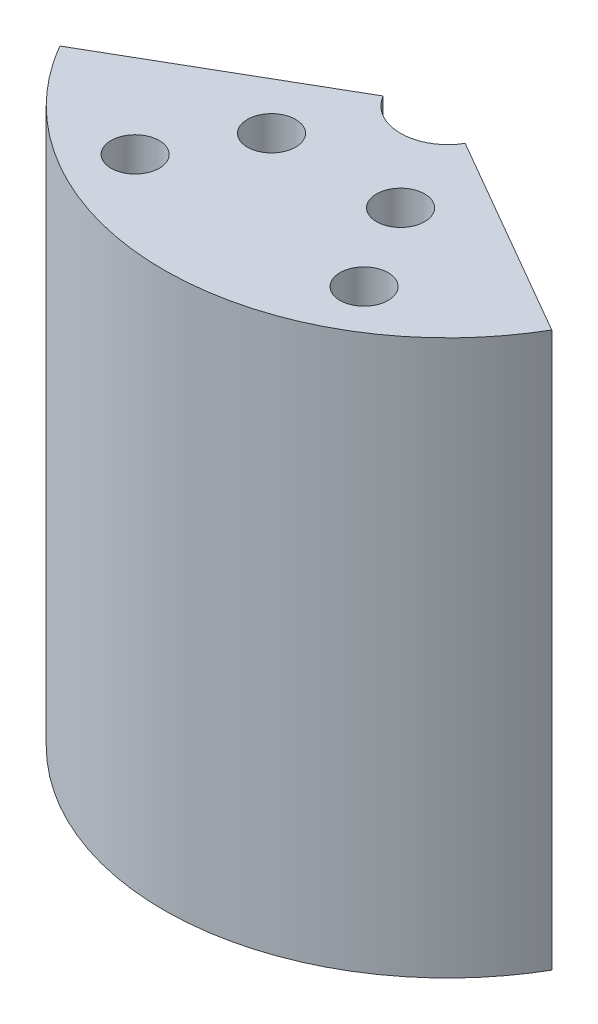
SolidWorks part; units mm, degrees
ref_plane "Front Plane" through (0, 0, 0) normal (0, 0, 1) x (1, 0, 0)
ref_plane "Top Plane" through (0, 0, 0) normal (0, 1, 0) x (1, 0, 0)
ref_plane "Right Plane" through (0, 0, 0) normal (1, 0, 0) x (0, 0, -1)
curve "Curve5"
  spline degree 1 poles (33250, -157953.272, 57590.689) (36750, -157953.272, 63652.867) knots 0 0 1 1
curve "Curve6"
  spline degree 1 poles (-33250, -157953.272, 57590.689) (-36750, -157953.272, 63652.867) knots 0 0 1 1
curve "Curve7"
  spline degree 1 poles (33250, 3112.16, 57590.689) (36750, 3112.16, 63652.867) knots 0 0 1 1
curve "Curve9"
  spline degree 1 poles (-33250, 3112.16, 57590.689) (-36750, 3112.16, 63652.867) knots 0 0 1 1
curve "Curve10"
  spline degree 1 poles (18750, -157953.272, 32475.953) (22250, -157953.272, 38538.13) knots 0 0 1 1
curve "Curve11"
  spline degree 1 poles (-18750, -157953.272, 32475.953) (-22250, -157953.272, 38538.13) knots 0 0 1 1
curve "Curve12"
  spline degree 1 poles (18750, 3112.16, 32475.953) (22250, 3112.16, 38538.13) knots 0 0 1 1
curve "Curve13"
  spline degree 1 poles (-18750, 3112.16, 32475.953) (-22250, 3112.16, 38538.13) knots 0 0 1 1
curve "Curve16"
  spline degree 1 poles (71447.096, -157953.272, 41250) (11907.849, -157953.272, 6875) knots 0 0 1 1
curve "Curve17"
  spline degree 1 poles (-71447.096, -157953.272, 41250) (-11907.849, -157953.272, 6875) knots 0 0 1 1
curve "Curve18"
  spline degree 1 poles (71447.096, 3112.16, 41250) (11907.849, 3112.16, 6875) knots 0 0 1 1
curve "Curve19"
  spline degree 1 poles (-11907.849, 3112.16, 6875) (-71447.096, 3112.16, 41250) knots 0 0 1 1
curve "Curve20"
  spline degree 1 poles (67826.113, -157953.272, -46966.673) (0, -157953.272, 0) knots 0 0 1 1
curve "Curve25"
  spline degree 1 poles (67826.113, 3112.16, -46966.673) (0, 3112.16, 0) knots 0 0 1 1
curve "Curve27"
  spline degree 3 poles (67826.113, 0, -46966.673) (71832.8446, 0, -40036.3374) (83609.5717, 0, -19666.4498) (93574.8958, 0, 18499.4968) (99605.6216, 0, 58154.7721) (101018.9906, 0, 82777.6883) (101543.573, 0, 91916.667) knots 0 0 0 0 0.165944 0.487747 0.809874 1 1 1 1
curve "Curve29"
  spline degree 3 poles (71447.096, -157953.272, 41250) (70846.8209, -157953.272, 42260.6958) (69646.2708, -157953.272, 44282.0874) (67683.2549, -157953.272, 47213.0963) (65605.9749, -157953.272, 50063.2727) (63406.3449, -157953.272, 52820.5514) (61091.5637, -157953.272, 55481.7315) (58665.0093, -157953.272, 58041.4616) (56131.3417, -157953.272, 60495.1976) (53495.1291, -157953.272, 62838.4229) (50761.2001, -157953.272, 65066.8628) (47934.5481, -157953.272, 67176.4488) (45020.3357, -157953.272, 69163.3252) (42023.8854, -157953.272, 71023.8629) (38950.6723, -157953.272, 72754.6647) (35806.3094, -157953.272, 74352.5684) (32596.5398, -157953.272, 75814.6529) (29327.2283, -157953.272, 77138.2518) (26004.3449, -157953.272, 78320.9429) (22633.9607, -157953.272, 79360.5703) (19222.2314, -157953.272, 80255.2301) (15775.3895, -157953.272, 81003.2908) (12299.7315, -157953.272, 81603.3869) (8801.6058, -157953.272, 82054.4198) (5287.4029, -157953.272, 82355.5679) (1763.5414, -157953.272, 82506.2784) (-1763.5414, -157953.272, 82506.2784) (-5287.4029, -157953.272, 82355.5679) (-8801.6058, -157953.272, 82054.4198) (-12299.7315, -157953.272, 81603.3869) (-15775.3895, -157953.272, 81003.2908) (-19222.2314, -157953.272, 80255.2301) (-22633.9607, -157953.272, 79360.5703) (-26004.3449, -157953.272, 78320.9429) (-29327.2283, -157953.272, 77138.2518) (-32596.5398, -157953.272, 75814.6529) (-35806.3094, -157953.272, 74352.5684) (-38950.6723, -157953.272, 72754.6647) (-42023.8854, -157953.272, 71023.8629) (-45020.3357, -157953.272, 69163.3252) (-47934.5481, -157953.272, 67176.4488) (-50761.2001, -157953.272, 65066.8628) (-53495.1291, -157953.272, 62838.4229) (-56131.3417, -157953.272, 60495.1976) (-58665.0093, -157953.272, 58041.4616) (-61091.5637, -157953.272, 55481.7315) (-63406.3449, -157953.272, 52820.5514) (-65605.9749, -157953.272, 50063.2727) (-67683.2549, -157953.272, 47213.0963) (-69646.2708, -157953.272, 44282.0874) (-70846.8209, -157953.272, 42260.6958) (-71447.096, -157953.272, 41250) knots 0 0 0 0 0.020408 0.040816 0.061224 0.081633 0.102041 0.122449 0.142857 0.163265 0.183673 0.204082 0.22449 0.244898 0.265306 0.285714 0.306122 0.326531 0.346939 0.367347 0.387755 0.408163 0.428571 0.44898 0.469388 0.489796 0.510204 0.530612 0.55102 0.571429 0.591837 0.612245 0.632653 0.653061 0.673469 0.693878 0.714286 0.734694 0.755102 0.77551 0.795918 0.816327 0.836735 0.857143 0.877551 0.897959 0.918367 0.938776 0.959184 0.979592 1 1 1 1
curve "Curve30"
  spline degree 3 poles (11907.849, -157953.272, 6875) (11807.803, -157953.272, 7043.4492) (11607.711, -157953.272, 7380.3474) (11280.5433, -157953.272, 7868.8496) (10934.3294, -157953.272, 8343.8788) (10567.7239, -157953.272, 8803.4251) (10181.9265, -157953.272, 9246.955) (9777.5017, -157953.272, 9673.5774) (9355.2232, -157953.272, 10082.5328) (8915.8543, -157953.272, 10473.0703) (8460.1999, -157953.272, 10844.4775) (7989.0912, -157953.272, 11196.0746) (7503.3891, -157953.272, 11527.2202) (7003.9814, -157953.272, 11837.3112) (6491.7785, -157953.272, 12125.7774) (5967.7179, -157953.272, 12392.0944) (5432.7569, -157953.272, 12635.7764) (4887.871, -157953.272, 12856.3745) (4334.0575, -157953.272, 13053.4915) (3772.3267, -157953.272, 13226.7617) (3203.705, -157953.272, 13375.8712) (2629.2315, -157953.272, 13500.548) (2049.9553, -157953.272, 13600.5649) (1466.9345, -157953.272, 13675.7363) (881.234, -157953.272, 13725.9278) (293.9237, -157953.272, 13751.0464) (-293.9237, -157953.272, 13751.0464) (-881.234, -157953.272, 13725.9278) (-1466.9345, -157953.272, 13675.7363) (-2049.9553, -157953.272, 13600.5649) (-2629.2315, -157953.272, 13500.548) (-3203.705, -157953.272, 13375.8712) (-3772.3267, -157953.272, 13226.7617) (-4334.0575, -157953.272, 13053.4915) (-4887.871, -157953.272, 12856.3745) (-5432.7569, -157953.272, 12635.7764) (-5967.7179, -157953.272, 12392.0944) (-6491.7785, -157953.272, 12125.7774) (-7003.9814, -157953.272, 11837.3112) (-7503.3891, -157953.272, 11527.2202) (-7989.0912, -157953.272, 11196.0746) (-8460.1999, -157953.272, 10844.4775) (-8915.8543, -157953.272, 10473.0703) (-9355.2232, -157953.272, 10082.5328) (-9777.5017, -157953.272, 9673.5774) (-10181.9265, -157953.272, 9246.955) (-10567.7239, -157953.272, 8803.4251) (-10934.3294, -157953.272, 8343.8788) (-11280.5433, -157953.272, 7868.8496) (-11607.711, -157953.272, 7380.3474) (-11807.803, -157953.272, 7043.4492) (-11907.849, -157953.272, 6875) knots 0 0 0 0 0.020408 0.040816 0.061224 0.081633 0.102041 0.122449 0.142857 0.163265 0.183673 0.204082 0.22449 0.244898 0.265306 0.285714 0.306122 0.326531 0.346939 0.367347 0.387755 0.408163 0.428571 0.44898 0.469388 0.489796 0.510204 0.530612 0.55102 0.571429 0.591837 0.612245 0.632653 0.653061 0.673469 0.693878 0.714286 0.734694 0.755102 0.77551 0.795918 0.816327 0.836735 0.857143 0.877551 0.897959 0.918367 0.938776 0.959184 0.979592 1 1 1 1
curve "Curve31"
  spline degree 3 poles (71447.096, 3112.16, 41250) (70846.8209, 3112.16, 42260.6958) (69646.2708, 3112.16, 44282.0874) (67683.2549, 3112.16, 47213.0963) (65605.9749, 3112.16, 50063.2727) (63406.3449, 3112.16, 52820.5514) (61091.5637, 3112.16, 55481.7315) (58665.0093, 3112.16, 58041.4616) (56131.3417, 3112.16, 60495.1976) (53495.1291, 3112.16, 62838.4229) (50761.2001, 3112.16, 65066.8628) (47934.5481, 3112.16, 67176.4488) (45020.3357, 3112.16, 69163.3252) (42023.8854, 3112.16, 71023.8629) (38950.6723, 3112.16, 72754.6647) (35806.3094, 3112.16, 74352.5684) (32596.5398, 3112.16, 75814.6529) (29327.2283, 3112.16, 77138.2518) (26004.3449, 3112.16, 78320.9429) (22633.9607, 3112.16, 79360.5703) (19222.2314, 3112.16, 80255.2301) (15775.3895, 3112.16, 81003.2908) (12299.7315, 3112.16, 81603.3869) (8801.6058, 3112.16, 82054.4198) (5287.4029, 3112.16, 82355.5679) (1763.5414, 3112.16, 82506.2784) (-1763.5414, 3112.16, 82506.2784) (-5287.4029, 3112.16, 82355.5679) (-8801.6058, 3112.16, 82054.4198) (-12299.7315, 3112.16, 81603.3869) (-15775.3895, 3112.16, 81003.2908) (-19222.2314, 3112.16, 80255.2301) (-22633.9607, 3112.16, 79360.5703) (-26004.3449, 3112.16, 78320.9429) (-29327.2283, 3112.16, 77138.2518) (-32596.5398, 3112.16, 75814.6529) (-35806.3094, 3112.16, 74352.5684) (-38950.6723, 3112.16, 72754.6647) (-42023.8854, 3112.16, 71023.8629) (-45020.3357, 3112.16, 69163.3252) (-47934.5481, 3112.16, 67176.4488) (-50761.2001, 3112.16, 65066.8628) (-53495.1291, 3112.16, 62838.4229) (-56131.3417, 3112.16, 60495.1976) (-58665.0093, 3112.16, 58041.4616) (-61091.5637, 3112.16, 55481.7315) (-63406.3449, 3112.16, 52820.5514) (-65605.9749, 3112.16, 50063.2727) (-67683.2549, 3112.16, 47213.0963) (-69646.2708, 3112.16, 44282.0874) (-70846.8209, 3112.16, 42260.6958) (-71447.096, 3112.16, 41250) knots 0 0 0 0 0.020408 0.040816 0.061224 0.081633 0.102041 0.122449 0.142857 0.163265 0.183673 0.204082 0.22449 0.244898 0.265306 0.285714 0.306122 0.326531 0.346939 0.367347 0.387755 0.408163 0.428571 0.44898 0.469388 0.489796 0.510204 0.530612 0.55102 0.571429 0.591837 0.612245 0.632653 0.653061 0.673469 0.693878 0.714286 0.734694 0.755102 0.77551 0.795918 0.816327 0.836735 0.857143 0.877551 0.897959 0.918367 0.938776 0.959184 0.979592 1 1 1 1
curve "Curve32"
  spline degree 3 poles (11907.849, 3112.16, 6875) (11807.803, 3112.16, 7043.4492) (11607.711, 3112.16, 7380.3474) (11280.5433, 3112.16, 7868.8496) (10934.3294, 3112.16, 8343.8788) (10567.7239, 3112.16, 8803.4251) (10181.9265, 3112.16, 9246.955) (9777.5017, 3112.16, 9673.5774) (9355.2232, 3112.16, 10082.5328) (8915.8543, 3112.16, 10473.0703) (8460.1999, 3112.16, 10844.4775) (7989.0912, 3112.16, 11196.0746) (7503.3891, 3112.16, 11527.2202) (7003.9814, 3112.16, 11837.3112) (6491.7785, 3112.16, 12125.7774) (5967.7179, 3112.16, 12392.0944) (5432.7569, 3112.16, 12635.7764) (4887.871, 3112.16, 12856.3745) (4334.0575, 3112.16, 13053.4915) (3772.3267, 3112.16, 13226.7617) (3203.705, 3112.16, 13375.8712) (2629.2315, 3112.16, 13500.548) (2049.9553, 3112.16, 13600.5649) (1466.9345, 3112.16, 13675.7363) (881.234, 3112.16, 13725.9278) (293.9237, 3112.16, 13751.0464) (-293.9237, 3112.16, 13751.0464) (-881.234, 3112.16, 13725.9278) (-1466.9345, 3112.16, 13675.7363) (-2049.9553, 3112.16, 13600.5649) (-2629.2315, 3112.16, 13500.548) (-3203.705, 3112.16, 13375.8712) (-3772.3267, 3112.16, 13226.7617) (-4334.0575, 3112.16, 13053.4915) (-4887.871, 3112.16, 12856.3745) (-5432.7569, 3112.16, 12635.7764) (-5967.7179, 3112.16, 12392.0944) (-6491.7785, 3112.16, 12125.7774) (-7003.9814, 3112.16, 11837.3112) (-7503.3891, 3112.16, 11527.2202) (-7989.0912, 3112.16, 11196.0746) (-8460.1999, 3112.16, 10844.4775) (-8915.8543, 3112.16, 10473.0703) (-9355.2232, 3112.16, 10082.5328) (-9777.5017, 3112.16, 9673.5774) (-10181.9265, 3112.16, 9246.955) (-10567.7239, 3112.16, 8803.4251) (-10934.3294, 3112.16, 8343.8788) (-11280.5433, 3112.16, 7868.8496) (-11607.711, 3112.16, 7380.3474) (-11807.803, 3112.16, 7043.4492) (-11907.849, 3112.16, 6875) knots 0 0 0 0 0.020408 0.040816 0.061224 0.081633 0.102041 0.122449 0.142857 0.163265 0.183673 0.204082 0.22449 0.244898 0.265306 0.285714 0.306122 0.326531 0.346939 0.367347 0.387755 0.408163 0.428571 0.44898 0.469388 0.489796 0.510204 0.530612 0.55102 0.571429 0.591837 0.612245 0.632653 0.653061 0.673469 0.693878 0.714286 0.734694 0.755102 0.77551 0.795918 0.816327 0.836735 0.857143 0.877551 0.897959 0.918367 0.938776 0.959184 0.979592 1 1 1 1
curve "Curve33"
  spline degree 3 poles (66490.2119, 3112.16, -1397.4309) (66504.8941, 3112.16, 0) (66490.2119, 3112.16, 1397.4309) (66446.1664, 3112.16, 2794.2445) (66372.7844, 3112.16, 4189.8244) (66270.0898, 3112.16, 5583.554) (66138.1343, 3112.16, 6974.8185) (65976.9749, 3112.16, 8363.0031) (65786.6803, 3112.16, 9747.4946) (65567.3377, 3112.16, 11127.6818) (65319.041, 3112.16, 12502.9553) (65041.9019, 3112.16, 13872.7081) (64736.0413, 3112.16, 15236.3351) (64401.5954, 3112.16, 16593.2339) (64038.7134, 3112.16, 17942.8059) (63647.5507, 3112.16, 19284.4543) (63228.2857, 3112.16, 20617.588) (62781.0993, 3112.16, 21941.6172) (62306.1905, 3112.16, 23255.9573) (61803.7692, 3112.16, 24560.0284) (61274.0587, 3112.16, 25853.255) (60717.2893, 3112.16, 27135.065) (60133.7098, 3112.16, 28404.8932) (59523.5764, 3112.16, 29662.1782) (58887.16, 3112.16, 30906.3655) (58224.7399, 3112.16, 32136.9054) (57536.6095, 3112.16, 33353.2547) (56823.072, 3112.16, 34554.8758) (56084.4435, 3112.16, 35741.2383) (55321.0501, 3112.16, 36911.8188) (54533.2289, 3112.16, 38066.1005) (53721.3251, 3112.16, 39203.5719) (52885.7025, 3112.16, 40323.734) (52026.7247, 3112.16, 41426.0884) (51144.7752, 3112.16, 42510.1518) (50240.2403, 3112.16, 43575.4429) (49313.5212, 3112.16, 44621.493) (48365.0267, 3112.16, 45647.8394) (47395.1749, 3112.16, 46654.0286) (46404.3952, 3112.16, 47639.6169) (45393.1248, 3112.16, 48604.1691) (44361.8098, 3112.16, 49547.2583) (43310.9062, 3112.16, 50468.4694) (42240.8781, 3112.16, 51367.3954) (41152.1964, 3112.16, 52243.6381) (40045.3432, 3112.16, 53096.8111) (38920.8085, 3112.16, 53926.5402) (37779.0861, 3112.16, 54732.4548) (36620.6825, 3112.16, 55514.203) (35446.1064, 3112.16, 56271.4348) (34255.8804, 3112.16, 57003.8213) (33050.527, 3112.16, 57711.0353) (31830.5798, 3112.16, 58392.7664) (30596.5766, 3112.16, 59048.7127) (29349.0632, 3112.16, 59678.5849) (28088.59, 3112.16, 60282.1047) (26815.7134, 3112.16, 60859.0048) (25530.9963, 3112.16, 61409.0322) (24235.0054, 3112.16, 61931.9434) (22928.3123, 3112.16, 62427.5048) (21611.4956, 3112.16, 62895.5034) (20285.1348, 3112.16, 63335.7256) (18949.8178, 3112.16, 63747.9838) (17606.1327, 3112.16, 64132.0909) (16254.6729, 3112.16, 64487.8789) (14896.0357, 3112.16, 64815.192) (13530.8207, 3112.16, 65113.8844) (12159.6307, 3112.16, 65383.8224) (10783.0718, 3112.16, 65624.892) (9401.751, 3112.16, 65836.9813) (8016.2791, 3112.16, 66019.9986) (6627.2675, 3112.16, 66173.864) (5235.3292, 3112.16, 66298.5095) (3841.079, 3112.16, 66393.878) (2445.1328, 3112.16, 66459.9303) (1048.1071, 3112.16, 66496.6348) (-349.3818, 3112.16, 66503.9764) (-1746.7163, 3112.16, 66481.9516) (-3143.2793, 3112.16, 66430.5711) (-4538.4543, 3112.16, 66349.856) (-5931.6255, 3112.16, 66239.8427) (-7322.1776, 3112.16, 66100.5811) (-8709.4961, 3112.16, 65932.1289) (-10092.9687, 3112.16, 65734.5651) (-11471.9844, 3112.16, 65507.973) (-12845.9346, 3112.16, 65252.455) (-14214.213, 3112.16, 64968.1248) (-15576.2141, 3112.16, 64655.1041) (-16931.3373, 3112.16, 64313.5351) (-18278.984, 3112.16, 63943.5672) (-19618.5592, 3112.16, 63545.3624) (-20949.4714, 3112.16, 63119.0984) (-22271.1332, 3112.16, 62664.9628) (-23582.9605, 3112.16, 62183.1564) (-24884.3746, 3112.16, 61673.8919) (-26174.8003, 3112.16, 61137.3937) (-27453.6673, 3112.16, 60573.8979) (-28720.4119, 3112.16, 59983.6551) (-29974.4751, 3112.16, 59366.9267) (-31215.3011, 3112.16, 58723.9803) (-32442.3447, 3112.16, 58055.1058) (-33655.0619, 3112.16, 57360.5945) (-34852.9176, 3112.16, 56640.7543) (-36035.3846, 3112.16, 55895.905) (-37201.9373, 3112.16, 55126.371) (-38352.0641, 3112.16, 54332.4966) (-39485.2547, 3112.16, 53514.6292) (-40601.0113, 3112.16, 52673.1326) (-41698.8386, 3112.16, 51808.3759) (-42778.2531, 3112.16, 50920.7428) (-43838.7775, 3112.16, 50010.624) (-44879.9452, 3112.16, 49078.4232) (-45901.2938, 3112.16, 48124.549) (-46902.3737, 3112.16, 47149.4246) (-47882.7441, 3112.16, 46153.482) (-48841.9695, 3112.16, 45137.1576) (-49779.6285, 3112.16, 44100.9028) (-50695.3062, 3112.16, 43045.1738) (-51588.5976, 3112.16, 41970.4371) (-52459.1084, 3112.16, 40877.1672) (-53306.4565, 3112.16, 39765.8486) (-54130.2646, 3112.16, 38636.9692) (-54930.1718, 3112.16, 37491.0295) (-55705.8215, 3112.16, 36328.5336) (-56456.8738, 3112.16, 35149.9966) (-57182.9977, 3112.16, 33955.9394) (-57883.8688, 3112.16, 32746.8867) (-58559.1814, 3112.16, 31523.3751) (-59208.6372, 3112.16, 30285.9439) (-59831.9447, 3112.16, 29035.1377) (-60428.8356, 3112.16, 27771.5118) (-60999.0411, 3112.16, 26495.6222) (-61542.3113, 3112.16, 25208.0329) (-62058.4062, 3112.16, 23909.313) (-62547.0971, 3112.16, 22600.0347) (-63008.1702, 3112.16, 21280.7773) (-63441.4199, 3112.16, 19952.1226) (-63846.6557, 3112.16, 18614.6576) (-64223.6996, 3112.16, 17268.9733) (-64572.3832, 3112.16, 15915.6631) (-64892.554, 3112.16, 14555.3252) (-65184.069, 3112.16, 13188.5596) (-65446.8018, 3112.16, 11815.9708) (-65680.6336, 3112.16, 10438.1641) (-65885.4639, 3112.16, 9055.7486) (-66061.2006, 3112.16, 7669.3342) (-66207.7678, 3112.16, 6279.5334) (-66325.0981, 3112.16, 4886.9592) (-66413.142, 3112.16, 3492.2274) (-66471.8577, 3112.16, 2095.9534) (-66501.2233, 3112.16, 698.7539) (-66501.2233, 3112.16, -698.7539) (-66471.8577, 3112.16, -2095.9534) (-66413.142, 3112.16, -3492.2274) (-66325.0981, 3112.16, -4886.9592) (-66207.7678, 3112.16, -6279.5334) (-66061.2006, 3112.16, -7669.3342) (-65885.4639, 3112.16, -9055.7486) (-65680.6336, 3112.16, -10438.1641) (-65446.8018, 3112.16, -11815.9708) (-65184.069, 3112.16, -13188.5596) (-64892.554, 3112.16, -14555.3252) (-64572.3832, 3112.16, -15915.6631) (-64223.6996, 3112.16, -17268.9733) (-63846.6557, 3112.16, -18614.6576) (-63441.4199, 3112.16, -19952.1226) (-63008.1702, 3112.16, -21280.7773) (-62547.0971, 3112.16, -22600.0347) (-62058.4062, 3112.16, -23909.313) (-61542.3113, 3112.16, -25208.0329) (-60999.0411, 3112.16, -26495.6222) (-60428.8356, 3112.16, -27771.5118) (-59831.9447, 3112.16, -29035.1377) (-59208.6372, 3112.16, -30285.9439) (-58559.1814, 3112.16, -31523.3751) (-57883.8688, 3112.16, -32746.8867) (-57182.9977, 3112.16, -33955.9394) (-56456.8738, 3112.16, -35149.9966) (-55705.8215, 3112.16, -36328.5336) (-54930.1718, 3112.16, -37491.0295) (-54130.2646, 3112.16, -38636.9692) (-53306.4565, 3112.16, -39765.8486) (-52459.1084, 3112.16, -40877.1672) (-51588.5976, 3112.16, -41970.4371) (-50695.3062, 3112.16, -43045.1738) (-49779.6285, 3112.16, -44100.9028) (-48841.9695, 3112.16, -45137.1576) (-47882.7441, 3112.16, -46153.482) (-46902.3737, 3112.16, -47149.4246) (-45901.2938, 3112.16, -48124.549) (-44879.9452, 3112.16, -49078.4232) (-43838.7775, 3112.16, -50010.624) (-42778.2531, 3112.16, -50920.7428) (-41698.8386, 3112.16, -51808.3759) (-40601.0113, 3112.16, -52673.1326) (-39485.2547, 3112.16, -53514.6292) (-38352.0641, 3112.16, -54332.4966) (-37201.9373, 3112.16, -55126.371) (-36035.3846, 3112.16, -55895.905) (-34852.9176, 3112.16, -56640.7543) (-33655.0619, 3112.16, -57360.5945) (-32442.3447, 3112.16, -58055.1058) (-31215.3011, 3112.16, -58723.9803) (-29974.4751, 3112.16, -59366.9267) (-28720.4119, 3112.16, -59983.6551) (-27453.6673, 3112.16, -60573.8979) (-26174.8003, 3112.16, -61137.3937) (-24884.3746, 3112.16, -61673.8919) (-23582.9605, 3112.16, -62183.1564) (-22271.1332, 3112.16, -62664.9628) (-20949.4714, 3112.16, -63119.0984) (-19618.5592, 3112.16, -63545.3624) (-18278.984, 3112.16, -63943.5672) (-16931.3373, 3112.16, -64313.5351) (-15576.2141, 3112.16, -64655.1041) (-14214.213, 3112.16, -64968.1248) (-12845.9346, 3112.16, -65252.455) (-11471.9844, 3112.16, -65507.973) (-10092.9687, 3112.16, -65734.5651) (-8709.4961, 3112.16, -65932.1289) (-7322.1776, 3112.16, -66100.5811) (-5931.6255, 3112.16, -66239.8427) (-4538.4543, 3112.16, -66349.856) (-3143.2793, 3112.16, -66430.5711) (-1746.7163, 3112.16, -66481.9516) (-349.3818, 3112.16, -66503.9764) (1048.1071, 3112.16, -66496.6348) (2445.1328, 3112.16, -66459.9303) (3841.079, 3112.16, -66393.878) (5235.3292, 3112.16, -66298.5095) (6627.2675, 3112.16, -66173.864) (8016.2791, 3112.16, -66019.9986) (9401.751, 3112.16, -65836.9813) (10783.0718, 3112.16, -65624.892) (12159.6307, 3112.16, -65383.8224) (13530.8207, 3112.16, -65113.8844) (14896.0357, 3112.16, -64815.192) (16254.6729, 3112.16, -64487.8789) (17606.1327, 3112.16, -64132.0909) (18949.8178, 3112.16, -63747.9838) (20285.1348, 3112.16, -63335.7256) (21611.4956, 3112.16, -62895.5034) (22928.3123, 3112.16, -62427.5048) (24235.0054, 3112.16, -61931.9434) (25530.9963, 3112.16, -61409.0322) (26815.7134, 3112.16, -60859.0048) (28088.59, 3112.16, -60282.1047) (29349.0632, 3112.16, -59678.5849) (30596.5766, 3112.16, -59048.7127) (31830.5798, 3112.16, -58392.7664) (33050.527, 3112.16, -57711.0353) (34255.8804, 3112.16, -57003.8213) (35446.1064, 3112.16, -56271.4348) (36620.6825, 3112.16, -55514.203) (37779.0861, 3112.16, -54732.4548) (38920.8085, 3112.16, -53926.5402) (40045.3432, 3112.16, -53096.8111) (41152.1964, 3112.16, -52243.6381) (42240.8781, 3112.16, -51367.3954) (43310.9062, 3112.16, -50468.4694) (44361.8098, 3112.16, -49547.2583) (45393.1248, 3112.16, -48604.1691) (46404.3952, 3112.16, -47639.6169) (47395.1749, 3112.16, -46654.0286) (48365.0267, 3112.16, -45647.8394) (49313.5212, 3112.16, -44621.493) (50240.2403, 3112.16, -43575.4429) (51144.7752, 3112.16, -42510.1518) (52026.7247, 3112.16, -41426.0884) (52885.7025, 3112.16, -40323.734) (53721.3251, 3112.16, -39203.5719) (54533.2289, 3112.16, -38066.1005) (55321.0501, 3112.16, -36911.8188) (56084.4435, 3112.16, -35741.2383) (56823.072, 3112.16, -34554.8758) (57536.6095, 3112.16, -33353.2547) (58224.7399, 3112.16, -32136.9054) (58887.16, 3112.16, -30906.3655) (59523.5764, 3112.16, -29662.1782) (60133.7098, 3112.16, -28404.8932) (60717.2893, 3112.16, -27135.065) (61274.0587, 3112.16, -25853.255) (61803.7692, 3112.16, -24560.0284) (62306.1905, 3112.16, -23255.9573) (62781.0993, 3112.16, -21941.6172) (63228.2857, 3112.16, -20617.588) (63647.5507, 3112.16, -19284.4543) (64038.7134, 3112.16, -17942.8059) (64401.5954, 3112.16, -16593.2339) (64736.0413, 3112.16, -15236.3351) (65041.9019, 3112.16, -13872.7081) (65319.041, 3112.16, -12502.9553) (65567.3377, 3112.16, -11127.6818) (65786.6803, 3112.16, -9747.4946) (65976.9749, 3112.16, -8363.0031) (66138.1343, 3112.16, -6974.8185) (66270.0898, 3112.16, -5583.554) (66372.7844, 3112.16, -4189.8244) (66446.1664, 3112.16, -2794.2445) (66490.2119, 3112.16, -1397.4309) (66504.8941, 3112.16, 0) (66490.2119, 3112.16, 1397.4309) knots -0.010033 -0.006689 -0.003344 0 0.003344 0.006689 0.010033 0.013378 0.016722 0.020067 0.023411 0.026756 0.0301 0.033445 0.036789 0.040134 0.043478 0.046823 0.050167 0.053512 0.056856 0.060201 0.063545 0.06689 0.070234 0.073579 0.076923 0.080268 0.083612 0.086957 0.090301 0.093645 0.09699 0.100334 0.103679 0.107023 0.110368 0.113712 0.117057 0.120401 0.123746 0.12709 0.130435 0.133779 0.137124 0.140468 0.143813 0.147157 0.150502 0.153846 0.157191 0.160535 0.16388 0.167224 0.170569 0.173913 0.177258 0.180602 0.183946 0.187291 0.190635 0.19398 0.197324 0.200669 0.204013 0.207358 0.210702 0.214047 0.217391 0.220736 0.22408 0.227425 0.230769 0.234114 0.237458 0.240803 0.244147 0.247492 0.250836 0.254181 0.257525 0.26087 0.264214 0.267559 0.270903 0.274247 0.277592 0.280936 0.284281 0.287625 0.29097 0.294314 0.297659 0.301003 0.304348 0.307692 0.311037 0.314381 0.317726 0.32107 0.324415 0.327759 0.331104 0.334448 0.337793 0.341137 0.344482 0.347826 0.351171 0.354515 0.35786 0.361204 0.364548 0.367893 0.371237 0.374582 0.377926 0.381271 0.384615 0.38796 0.391304 0.394649 0.397993 0.401338 0.404682 0.408027 0.411371 0.414716 0.41806 0.421405 0.424749 0.428094 0.431438 0.434783 0.438127 0.441472 0.444816 0.448161 0.451505 0.454849 0.458194 0.461538 0.464883 0.468227 0.471572 0.474916 0.478261 0.481605 0.48495 0.488294 0.491639 0.494983 0.498328 0.501672 0.505017 0.508361 0.511706 0.51505 0.518395 0.521739 0.525084 0.528428 0.531773 0.535117 0.538462 0.541806 0.545151 0.548495 0.551839 0.555184 0.558528 0.561873 0.565217 0.568562 0.571906 0.575251 0.578595 0.58194 0.585284 0.588629 0.591973 0.595318 0.598662 0.602007 0.605351 0.608696 0.61204 0.615385 0.618729 0.622074 0.625418 0.628763 0.632107 0.635452 0.638796 0.64214 0.645485 0.648829 0.652174 0.655518 0.658863 0.662207 0.665552 0.668896 0.672241 0.675585 0.67893 0.682274 0.685619 0.688963 0.692308 0.695652 0.698997 0.702341 0.705686 0.70903 0.712375 0.715719 0.719064 0.722408 0.725753 0.729097 0.732441 0.735786 0.73913 0.742475 0.745819 0.749164 0.752508 0.755853 0.759197 0.762542 0.765886 0.769231 0.772575 0.77592 0.779264 0.782609 0.785953 0.789298 0.792642 0.795987 0.799331 0.802676 0.80602 0.809365 0.812709 0.816054 0.819398 0.822742 0.826087 0.829431 0.832776 0.83612 0.839465 0.842809 0.846154 0.849498 0.852843 0.856187 0.859532 0.862876 0.866221 0.869565 0.87291 0.876254 0.879599 0.882943 0.886288 0.889632 0.892977 0.896321 0.899666 0.90301 0.906355 0.909699 0.913043 0.916388 0.919732 0.923077 0.926421 0.929766 0.93311 0.936455 0.939799 0.943144 0.946488 0.949833 0.953177 0.956522 0.959866 0.963211 0.966555 0.9699 0.973244 0.976589 0.979933 0.983278 0.986622 0.989967 0.993311 0.996656 1 1.003344 1.006689 1.010033 periodic
curve "Curve34"
  spline degree 3 poles (-71447.096, -157953.272, 41250) (-119654.1141, -167228.3585, 58604.135) (-176188.8326, -178105.7043, 78956.1746) (-151484.4484, -148962.176, 97388.6003) (-147845.433, -144669.264, 100103.741) knots 0 0 0 0 0.852698 1 1 1 1
ref_plane "Plane1" through (0, 3112.16, 0) normal (0, 1, 0) x (-1, 0, 0)
sketch3d "3DSketch3"
  line L0 (0, -157953.272, 0) -> (0, 3112.16, 0) construction
  line L1 (-71447.096, -157953.272, 41250) -> (-11907.849, -157953.272, 6875)
  line L2 (-71447.096, -157953.272, 41250) -> (-11907.849, -157953.272, 6875)
  line L3 (-18750, -157953.272, 32475.953) -> (-22250, -157953.272, 38538.13)
  line L4 (-18750, -157953.272, 32475.953) -> (-22250, -157953.272, 38538.13)
  line L5 (18750, -157953.272, 32475.953) -> (22250, -157953.272, 38538.13)
  line L6 (18750, -157953.272, 32475.953) -> (22250, -157953.272, 38538.13)
  line L7 (33250, -157953.272, 57590.689) -> (36750, -157953.272, 63652.867)
  line L8 (33250, -157953.272, 57590.689) -> (36750, -157953.272, 63652.867)
  line L9 (71447.096, -157953.272, 41250) -> (11907.849, -157953.272, 6875)
  line L10 (71447.096, -157953.272, 41250) -> (11907.849, -157953.272, 6875)
  line L11 (-33250, -157953.272, 57590.689) -> (-36750, -157953.272, 63652.867)
  line L12 (-33250, -157953.272, 57590.689) -> (-36750, -157953.272, 63652.867)
  line L13 (67826.113, -157953.272, -46966.673) -> (0, -157953.272, 0)
  line L14 (67826.113, -157953.272, -46966.673) -> (0, -157953.272, 0)
  line L15 (-11907.849, 3112.16, 6875) -> (-71447.096, 3112.16, 41250)
  line L16 (-11907.849, 3112.16, 6875) -> (-71447.096, 3112.16, 41250)
  line L17 (71447.096, 3112.16, 41250) -> (11907.849, 3112.16, 6875)
  line L18 (71447.096, 3112.16, 41250) -> (11907.849, 3112.16, 6875)
  line L19 (33250, 3112.16, 57590.689) -> (36750, 3112.16, 63652.867)
  line L20 (33250, 3112.16, 57590.689) -> (36750, 3112.16, 63652.867)
  line L21 (18750, 3112.16, 32475.953) -> (22250, 3112.16, 38538.13)
  line L22 (18750, 3112.16, 32475.953) -> (22250, 3112.16, 38538.13)
  line L23 (-18750, 3112.16, 32475.953) -> (-22250, 3112.16, 38538.13)
  line L24 (-18750, 3112.16, 32475.953) -> (-22250, 3112.16, 38538.13)
  line L25 (-33250, 3112.16, 57590.689) -> (-36750, 3112.16, 63652.867)
  line L26 (-33250, 3112.16, 57590.689) -> (-36750, 3112.16, 63652.867)
  line L27 (67826.113, 3112.16, -46966.673) -> (0, 3112.16, 0)
  line L28 (67826.113, 3112.16, -46966.673) -> (0, 3112.16, 0)
  circle A0 centre (33250, -157953.272, 57590.689) radius 7000.0002
  circle A1 centre (18750, -157953.272, 32475.953) radius 6999.9993
  circle A2 centre (-18750, -157953.272, 32475.953) radius 6999.9993
  circle A3 centre (-33250, -157953.272, 57590.689) radius 7000.0002
  spline S1 degree 3 poles (74076.3652, -157953.272, 37000.5832) (72494.0612, -157953.272, 39361.9368) (70573.6651, -157953.272, 42897.3809) (67683.2549, -157953.272, 47213.0963) (65605.9749, -157953.272, 50063.2727) (63406.3449, -157953.272, 52820.5514) (61091.5637, -157953.272, 55481.7315) (58665.0093, -157953.272, 58041.4616) (56131.3417, -157953.272, 60495.1976) (53495.1291, -157953.272, 62838.4229) (50761.2001, -157953.272, 65066.8628) (47934.5481, -157953.272, 67176.4488) (45020.3357, -157953.272, 69163.3252) (42023.8854, -157953.272, 71023.8629) (38950.6723, -157953.272, 72754.6647) (35806.3094, -157953.272, 74352.5684) (32596.5398, -157953.272, 75814.6529) (29327.2283, -157953.272, 77138.2518) (26004.3449, -157953.272, 78320.9429) (22633.9607, -157953.272, 79360.5703) (19222.2314, -157953.272, 80255.2301) (15775.3895, -157953.272, 81003.2908) (12299.7315, -157953.272, 81603.3869) (8801.6058, -157953.272, 82054.4198) (5287.4029, -157953.272, 82355.5679) (1763.5414, -157953.272, 82506.2784) (-1763.5414, -157953.272, 82506.2784) (-5287.4029, -157953.272, 82355.5679) (-8801.6058, -157953.272, 82054.4198) (-12299.7315, -157953.272, 81603.3869) (-15775.3895, -157953.272, 81003.2908) (-19222.2314, -157953.272, 80255.2301) (-22633.9607, -157953.272, 79360.5703) (-26004.3449, -157953.272, 78320.9429) (-29327.2283, -157953.272, 77138.2518) (-32596.5398, -157953.272, 75814.6529) (-35806.3094, -157953.272, 74352.5684) (-38950.6723, -157953.272, 72754.6647) (-42023.8854, -157953.272, 71023.8629) (-45020.3357, -157953.272, 69163.3252) (-47934.5481, -157953.272, 67176.4488) (-50761.2001, -157953.272, 65066.8628) (-53495.1291, -157953.272, 62838.4229) (-56131.3417, -157953.272, 60495.1976) (-58665.0093, -157953.272, 58041.4616) (-61091.5637, -157953.272, 55481.7315) (-63406.3449, -157953.272, 52820.5514) (-65605.9749, -157953.272, 50063.2727) (-67683.2549, -157953.272, 47213.0963) (-70573.6793, -157953.272, 42897.3597) (-72494.0856, -157953.272, 39361.8919) (-74076.4078, -157953.272, 37000.5196) knots -0.028924 -0.028924 -0.028924 -0.028924 0.020408 0.040816 0.061224 0.081633 0.102041 0.122449 0.142857 0.163265 0.183673 0.204082 0.22449 0.244898 0.265306 0.285714 0.306122 0.326531 0.346939 0.367347 0.387755 0.408163 0.428571 0.44898 0.469388 0.489796 0.510204 0.530612 0.55102 0.571429 0.591837 0.612245 0.632653 0.653061 0.673469 0.693878 0.714286 0.734694 0.755102 0.77551 0.795918 0.816327 0.836735 0.857143 0.877551 0.897959 0.918367 0.938776 0.959184 0.979592 1.028925 1.028925 1.028925 1.028925 only from (71447.096, -157953.272, 41250) to (-71447.096, -157953.272, 41250)
  spline S2 degree 3 poles (71447.096, -157953.272, 41250) (70846.8209, -157953.272, 42260.6958) (69646.2708, -157953.272, 44282.0874) (67683.2549, -157953.272, 47213.0963) (65605.9749, -157953.272, 50063.2727) (63406.3449, -157953.272, 52820.5514) (61091.5637, -157953.272, 55481.7315) (58665.0093, -157953.272, 58041.4616) (56131.3417, -157953.272, 60495.1976) (53495.1291, -157953.272, 62838.4229) (50761.2001, -157953.272, 65066.8628) (47934.5481, -157953.272, 67176.4488) (45020.3357, -157953.272, 69163.3252) (42023.8854, -157953.272, 71023.8629) (38950.6723, -157953.272, 72754.6647) (35806.3094, -157953.272, 74352.5684) (32596.5398, -157953.272, 75814.6529) (29327.2283, -157953.272, 77138.2518) (26004.3449, -157953.272, 78320.9429) (22633.9607, -157953.272, 79360.5703) (19222.2314, -157953.272, 80255.2301) (15775.3895, -157953.272, 81003.2908) (12299.7315, -157953.272, 81603.3869) (8801.6058, -157953.272, 82054.4198) (5287.4029, -157953.272, 82355.5679) (1763.5414, -157953.272, 82506.2784) (-1763.5414, -157953.272, 82506.2784) (-5287.4029, -157953.272, 82355.5679) (-8801.6058, -157953.272, 82054.4198) (-12299.7315, -157953.272, 81603.3869) (-15775.3895, -157953.272, 81003.2908) (-19222.2314, -157953.272, 80255.2301) (-22633.9607, -157953.272, 79360.5703) (-26004.3449, -157953.272, 78320.9429) (-29327.2283, -157953.272, 77138.2518) (-32596.5398, -157953.272, 75814.6529) (-35806.3094, -157953.272, 74352.5684) (-38950.6723, -157953.272, 72754.6647) (-42023.8854, -157953.272, 71023.8629) (-45020.3357, -157953.272, 69163.3252) (-47934.5481, -157953.272, 67176.4488) (-50761.2001, -157953.272, 65066.8628) (-53495.1291, -157953.272, 62838.4229) (-56131.3417, -157953.272, 60495.1976) (-58665.0093, -157953.272, 58041.4616) (-61091.5637, -157953.272, 55481.7315) (-63406.3449, -157953.272, 52820.5514) (-65605.9749, -157953.272, 50063.2727) (-67683.2549, -157953.272, 47213.0963) (-69646.2708, -157953.272, 44282.0874) (-70846.8209, -157953.272, 42260.6958) (-71447.096, -157953.272, 41250) knots 0 0 0 0 0.020408 0.040816 0.061224 0.081633 0.102041 0.122449 0.142857 0.163265 0.183673 0.204082 0.22449 0.244898 0.265306 0.285714 0.306122 0.326531 0.346939 0.367347 0.387755 0.408163 0.428571 0.44898 0.469388 0.489796 0.510204 0.530612 0.55102 0.571429 0.591837 0.612245 0.632653 0.653061 0.673469 0.693878 0.714286 0.734694 0.755102 0.77551 0.795918 0.816327 0.836735 0.857143 0.877551 0.897959 0.918367 0.938776 0.959184 0.979592 1 1 1 1
  spline S3 degree 3 poles (15869.0157, -157953.272, 4277.1823) (13030.7225, -157953.272, 4427.9523) (12405.7025, -157953.272, 6188.8468) (11280.5433, -157953.272, 7868.8496) (10934.3294, -157953.272, 8343.8788) (10567.7239, -157953.272, 8803.4251) (10181.9265, -157953.272, 9246.955) (9777.5017, -157953.272, 9673.5774) (9355.2232, -157953.272, 10082.5328) (8915.8543, -157953.272, 10473.0703) (8460.1999, -157953.272, 10844.4775) (7989.0912, -157953.272, 11196.0746) (7503.3891, -157953.272, 11527.2202) (7003.9814, -157953.272, 11837.3112) (6491.7785, -157953.272, 12125.7774) (5967.7179, -157953.272, 12392.0944) (5432.7569, -157953.272, 12635.7764) (4887.871, -157953.272, 12856.3745) (4334.0575, -157953.272, 13053.4915) (3772.3267, -157953.272, 13226.7617) (3203.705, -157953.272, 13375.8712) (2629.2315, -157953.272, 13500.548) (2049.9553, -157953.272, 13600.5649) (1466.9345, -157953.272, 13675.7363) (881.234, -157953.272, 13725.9278) (293.9237, -157953.272, 13751.0464) (-293.9237, -157953.272, 13751.0464) (-881.234, -157953.272, 13725.9278) (-1466.9345, -157953.272, 13675.7363) (-2049.9553, -157953.272, 13600.5649) (-2629.2315, -157953.272, 13500.548) (-3203.705, -157953.272, 13375.8712) (-3772.3267, -157953.272, 13226.7617) (-4334.0575, -157953.272, 13053.4915) (-4887.871, -157953.272, 12856.3745) (-5432.7569, -157953.272, 12635.7764) (-5967.7179, -157953.272, 12392.0944) (-6491.7785, -157953.272, 12125.7774) (-7003.9814, -157953.272, 11837.3112) (-7503.3891, -157953.272, 11527.2202) (-7989.0912, -157953.272, 11196.0746) (-8460.1999, -157953.272, 10844.4775) (-8915.8543, -157953.272, 10473.0703) (-9355.2232, -157953.272, 10082.5328) (-9777.5017, -157953.272, 9673.5774) (-10181.9265, -157953.272, 9246.955) (-10567.7239, -157953.272, 8803.4251) (-10934.3294, -157953.272, 8343.8788) (-11280.5433, -157953.272, 7868.8496) (-12405.7015, -157953.272, 6188.8483) (-13030.7212, -157953.272, 4427.956) (-15869.0059, -157953.272, 4277.1828) knots -0.149332 -0.149332 -0.149332 -0.149332 0.020408 0.040816 0.061224 0.081633 0.102041 0.122449 0.142857 0.163265 0.183673 0.204082 0.22449 0.244898 0.265306 0.285714 0.306122 0.326531 0.346939 0.367347 0.387755 0.408163 0.428571 0.44898 0.469388 0.489796 0.510204 0.530612 0.55102 0.571429 0.591837 0.612245 0.632653 0.653061 0.673469 0.693878 0.714286 0.734694 0.755102 0.77551 0.795918 0.816327 0.836735 0.857143 0.877551 0.897959 0.918367 0.938776 0.959184 0.979592 1.149332 1.149332 1.149332 1.149332 only from (11907.849, -157953.272, 6875) to (-11907.849, -157953.272, 6875)
  spline S4 degree 3 poles (11907.849, -157953.272, 6875) (11807.803, -157953.272, 7043.4492) (11607.711, -157953.272, 7380.3474) (11280.5433, -157953.272, 7868.8496) (10934.3294, -157953.272, 8343.8788) (10567.7239, -157953.272, 8803.4251) (10181.9265, -157953.272, 9246.955) (9777.5017, -157953.272, 9673.5774) (9355.2232, -157953.272, 10082.5328) (8915.8543, -157953.272, 10473.0703) (8460.1999, -157953.272, 10844.4775) (7989.0912, -157953.272, 11196.0746) (7503.3891, -157953.272, 11527.2202) (7003.9814, -157953.272, 11837.3112) (6491.7785, -157953.272, 12125.7774) (5967.7179, -157953.272, 12392.0944) (5432.7569, -157953.272, 12635.7764) (4887.871, -157953.272, 12856.3745) (4334.0575, -157953.272, 13053.4915) (3772.3267, -157953.272, 13226.7617) (3203.705, -157953.272, 13375.8712) (2629.2315, -157953.272, 13500.548) (2049.9553, -157953.272, 13600.5649) (1466.9345, -157953.272, 13675.7363) (881.234, -157953.272, 13725.9278) (293.9237, -157953.272, 13751.0464) (-293.9237, -157953.272, 13751.0464) (-881.234, -157953.272, 13725.9278) (-1466.9345, -157953.272, 13675.7363) (-2049.9553, -157953.272, 13600.5649) (-2629.2315, -157953.272, 13500.548) (-3203.705, -157953.272, 13375.8712) (-3772.3267, -157953.272, 13226.7617) (-4334.0575, -157953.272, 13053.4915) (-4887.871, -157953.272, 12856.3745) (-5432.7569, -157953.272, 12635.7764) (-5967.7179, -157953.272, 12392.0944) (-6491.7785, -157953.272, 12125.7774) (-7003.9814, -157953.272, 11837.3112) (-7503.3891, -157953.272, 11527.2202) (-7989.0912, -157953.272, 11196.0746) (-8460.1999, -157953.272, 10844.4775) (-8915.8543, -157953.272, 10473.0703) (-9355.2232, -157953.272, 10082.5328) (-9777.5017, -157953.272, 9673.5774) (-10181.9265, -157953.272, 9246.955) (-10567.7239, -157953.272, 8803.4251) (-10934.3294, -157953.272, 8343.8788) (-11280.5433, -157953.272, 7868.8496) (-11607.711, -157953.272, 7380.3474) (-11807.803, -157953.272, 7043.4492) (-11907.849, -157953.272, 6875) knots 0 0 0 0 0.020408 0.040816 0.061224 0.081633 0.102041 0.122449 0.142857 0.163265 0.183673 0.204082 0.22449 0.244898 0.265306 0.285714 0.306122 0.326531 0.346939 0.367347 0.387755 0.408163 0.428571 0.44898 0.469388 0.489796 0.510204 0.530612 0.55102 0.571429 0.591837 0.612245 0.632653 0.653061 0.673469 0.693878 0.714286 0.734694 0.755102 0.77551 0.795918 0.816327 0.836735 0.857143 0.877551 0.897959 0.918367 0.938776 0.959184 0.979592 1 1 1 1
  spline S5 degree 3 poles (15869.0157, 3112.16, 4277.1823) (13030.7225, 3112.16, 4427.9523) (12405.7025, 3112.16, 6188.8468) (11280.5433, 3112.16, 7868.8496) (10934.3294, 3112.16, 8343.8788) (10567.7239, 3112.16, 8803.4251) (10181.9265, 3112.16, 9246.955) (9777.5017, 3112.16, 9673.5774) (9355.2232, 3112.16, 10082.5328) (8915.8543, 3112.16, 10473.0703) (8460.1999, 3112.16, 10844.4775) (7989.0912, 3112.16, 11196.0746) (7503.3891, 3112.16, 11527.2202) (7003.9814, 3112.16, 11837.3112) (6491.7785, 3112.16, 12125.7774) (5967.7179, 3112.16, 12392.0944) (5432.7569, 3112.16, 12635.7764) (4887.871, 3112.16, 12856.3745) (4334.0575, 3112.16, 13053.4915) (3772.3267, 3112.16, 13226.7617) (3203.705, 3112.16, 13375.8712) (2629.2315, 3112.16, 13500.548) (2049.9553, 3112.16, 13600.5649) (1466.9345, 3112.16, 13675.7363) (881.234, 3112.16, 13725.9278) (293.9237, 3112.16, 13751.0464) (-293.9237, 3112.16, 13751.0464) (-881.234, 3112.16, 13725.9278) (-1466.9345, 3112.16, 13675.7363) (-2049.9553, 3112.16, 13600.5649) (-2629.2315, 3112.16, 13500.548) (-3203.705, 3112.16, 13375.8712) (-3772.3267, 3112.16, 13226.7617) (-4334.0575, 3112.16, 13053.4915) (-4887.871, 3112.16, 12856.3745) (-5432.7569, 3112.16, 12635.7764) (-5967.7179, 3112.16, 12392.0944) (-6491.7785, 3112.16, 12125.7774) (-7003.9814, 3112.16, 11837.3112) (-7503.3891, 3112.16, 11527.2202) (-7989.0912, 3112.16, 11196.0746) (-8460.1999, 3112.16, 10844.4775) (-8915.8543, 3112.16, 10473.0703) (-9355.2232, 3112.16, 10082.5328) (-9777.5017, 3112.16, 9673.5774) (-10181.9265, 3112.16, 9246.955) (-10567.7239, 3112.16, 8803.4251) (-10934.3294, 3112.16, 8343.8788) (-11280.5433, 3112.16, 7868.8496) (-12405.7015, 3112.16, 6188.8483) (-13030.7212, 3112.16, 4427.956) (-15869.0059, 3112.16, 4277.1828) knots -0.149332 -0.149332 -0.149332 -0.149332 0.020408 0.040816 0.061224 0.081633 0.102041 0.122449 0.142857 0.163265 0.183673 0.204082 0.22449 0.244898 0.265306 0.285714 0.306122 0.326531 0.346939 0.367347 0.387755 0.408163 0.428571 0.44898 0.469388 0.489796 0.510204 0.530612 0.55102 0.571429 0.591837 0.612245 0.632653 0.653061 0.673469 0.693878 0.714286 0.734694 0.755102 0.77551 0.795918 0.816327 0.836735 0.857143 0.877551 0.897959 0.918367 0.938776 0.959184 0.979592 1.149332 1.149332 1.149332 1.149332 only from (11907.849, 3112.16, 6875) to (-11907.849, 3112.16, 6875)
  spline S6 degree 3 poles (11907.849, 3112.16, 6875) (11807.803, 3112.16, 7043.4492) (11607.711, 3112.16, 7380.3474) (11280.5433, 3112.16, 7868.8496) (10934.3294, 3112.16, 8343.8788) (10567.7239, 3112.16, 8803.4251) (10181.9265, 3112.16, 9246.955) (9777.5017, 3112.16, 9673.5774) (9355.2232, 3112.16, 10082.5328) (8915.8543, 3112.16, 10473.0703) (8460.1999, 3112.16, 10844.4775) (7989.0912, 3112.16, 11196.0746) (7503.3891, 3112.16, 11527.2202) (7003.9814, 3112.16, 11837.3112) (6491.7785, 3112.16, 12125.7774) (5967.7179, 3112.16, 12392.0944) (5432.7569, 3112.16, 12635.7764) (4887.871, 3112.16, 12856.3745) (4334.0575, 3112.16, 13053.4915) (3772.3267, 3112.16, 13226.7617) (3203.705, 3112.16, 13375.8712) (2629.2315, 3112.16, 13500.548) (2049.9553, 3112.16, 13600.5649) (1466.9345, 3112.16, 13675.7363) (881.234, 3112.16, 13725.9278) (293.9237, 3112.16, 13751.0464) (-293.9237, 3112.16, 13751.0464) (-881.234, 3112.16, 13725.9278) (-1466.9345, 3112.16, 13675.7363) (-2049.9553, 3112.16, 13600.5649) (-2629.2315, 3112.16, 13500.548) (-3203.705, 3112.16, 13375.8712) (-3772.3267, 3112.16, 13226.7617) (-4334.0575, 3112.16, 13053.4915) (-4887.871, 3112.16, 12856.3745) (-5432.7569, 3112.16, 12635.7764) (-5967.7179, 3112.16, 12392.0944) (-6491.7785, 3112.16, 12125.7774) (-7003.9814, 3112.16, 11837.3112) (-7503.3891, 3112.16, 11527.2202) (-7989.0912, 3112.16, 11196.0746) (-8460.1999, 3112.16, 10844.4775) (-8915.8543, 3112.16, 10473.0703) (-9355.2232, 3112.16, 10082.5328) (-9777.5017, 3112.16, 9673.5774) (-10181.9265, 3112.16, 9246.955) (-10567.7239, 3112.16, 8803.4251) (-10934.3294, 3112.16, 8343.8788) (-11280.5433, 3112.16, 7868.8496) (-11607.711, 3112.16, 7380.3474) (-11807.803, 3112.16, 7043.4492) (-11907.849, 3112.16, 6875) knots 0 0 0 0 0.020408 0.040816 0.061224 0.081633 0.102041 0.122449 0.142857 0.163265 0.183673 0.204082 0.22449 0.244898 0.265306 0.285714 0.306122 0.326531 0.346939 0.367347 0.387755 0.408163 0.428571 0.44898 0.469388 0.489796 0.510204 0.530612 0.55102 0.571429 0.591837 0.612245 0.632653 0.653061 0.673469 0.693878 0.714286 0.734694 0.755102 0.77551 0.795918 0.816327 0.836735 0.857143 0.877551 0.897959 0.918367 0.938776 0.959184 0.979592 1 1 1 1
  spline S7 degree 3 poles (74076.3652, 3112.16, 37000.5832) (72494.0612, 3112.16, 39361.9368) (70573.6651, 3112.16, 42897.3809) (67683.2549, 3112.16, 47213.0963) (65605.9749, 3112.16, 50063.2727) (63406.3449, 3112.16, 52820.5514) (61091.5637, 3112.16, 55481.7315) (58665.0093, 3112.16, 58041.4616) (56131.3417, 3112.16, 60495.1976) (53495.1291, 3112.16, 62838.4229) (50761.2001, 3112.16, 65066.8628) (47934.5481, 3112.16, 67176.4488) (45020.3357, 3112.16, 69163.3252) (42023.8854, 3112.16, 71023.8629) (38950.6723, 3112.16, 72754.6647) (35806.3094, 3112.16, 74352.5684) (32596.5398, 3112.16, 75814.6529) (29327.2283, 3112.16, 77138.2518) (26004.3449, 3112.16, 78320.9429) (22633.9607, 3112.16, 79360.5703) (19222.2314, 3112.16, 80255.2301) (15775.3895, 3112.16, 81003.2908) (12299.7315, 3112.16, 81603.3869) (8801.6058, 3112.16, 82054.4198) (5287.4029, 3112.16, 82355.5679) (1763.5414, 3112.16, 82506.2784) (-1763.5414, 3112.16, 82506.2784) (-5287.4029, 3112.16, 82355.5679) (-8801.6058, 3112.16, 82054.4198) (-12299.7315, 3112.16, 81603.3869) (-15775.3895, 3112.16, 81003.2908) (-19222.2314, 3112.16, 80255.2301) (-22633.9607, 3112.16, 79360.5703) (-26004.3449, 3112.16, 78320.9429) (-29327.2283, 3112.16, 77138.2518) (-32596.5398, 3112.16, 75814.6529) (-35806.3094, 3112.16, 74352.5684) (-38950.6723, 3112.16, 72754.6647) (-42023.8854, 3112.16, 71023.8629) (-45020.3357, 3112.16, 69163.3252) (-47934.5481, 3112.16, 67176.4488) (-50761.2001, 3112.16, 65066.8628) (-53495.1291, 3112.16, 62838.4229) (-56131.3417, 3112.16, 60495.1976) (-58665.0093, 3112.16, 58041.4616) (-61091.5637, 3112.16, 55481.7315) (-63406.3449, 3112.16, 52820.5514) (-65605.9749, 3112.16, 50063.2727) (-67683.2549, 3112.16, 47213.0963) (-70573.6793, 3112.16, 42897.3597) (-72494.0856, 3112.16, 39361.8919) (-74076.4078, 3112.16, 37000.5196) knots -0.028924 -0.028924 -0.028924 -0.028924 0.020408 0.040816 0.061224 0.081633 0.102041 0.122449 0.142857 0.163265 0.183673 0.204082 0.22449 0.244898 0.265306 0.285714 0.306122 0.326531 0.346939 0.367347 0.387755 0.408163 0.428571 0.44898 0.469388 0.489796 0.510204 0.530612 0.55102 0.571429 0.591837 0.612245 0.632653 0.653061 0.673469 0.693878 0.714286 0.734694 0.755102 0.77551 0.795918 0.816327 0.836735 0.857143 0.877551 0.897959 0.918367 0.938776 0.959184 0.979592 1.028925 1.028925 1.028925 1.028925 only from (71447.096, 3112.16, 41250) to (-71447.096, 3112.16, 41250)
  spline S8 degree 3 poles (71447.096, 3112.16, 41250) (70846.8209, 3112.16, 42260.6958) (69646.2708, 3112.16, 44282.0874) (67683.2549, 3112.16, 47213.0963) (65605.9749, 3112.16, 50063.2727) (63406.3449, 3112.16, 52820.5514) (61091.5637, 3112.16, 55481.7315) (58665.0093, 3112.16, 58041.4616) (56131.3417, 3112.16, 60495.1976) (53495.1291, 3112.16, 62838.4229) (50761.2001, 3112.16, 65066.8628) (47934.5481, 3112.16, 67176.4488) (45020.3357, 3112.16, 69163.3252) (42023.8854, 3112.16, 71023.8629) (38950.6723, 3112.16, 72754.6647) (35806.3094, 3112.16, 74352.5684) (32596.5398, 3112.16, 75814.6529) (29327.2283, 3112.16, 77138.2518) (26004.3449, 3112.16, 78320.9429) (22633.9607, 3112.16, 79360.5703) (19222.2314, 3112.16, 80255.2301) (15775.3895, 3112.16, 81003.2908) (12299.7315, 3112.16, 81603.3869) (8801.6058, 3112.16, 82054.4198) (5287.4029, 3112.16, 82355.5679) (1763.5414, 3112.16, 82506.2784) (-1763.5414, 3112.16, 82506.2784) (-5287.4029, 3112.16, 82355.5679) (-8801.6058, 3112.16, 82054.4198) (-12299.7315, 3112.16, 81603.3869) (-15775.3895, 3112.16, 81003.2908) (-19222.2314, 3112.16, 80255.2301) (-22633.9607, 3112.16, 79360.5703) (-26004.3449, 3112.16, 78320.9429) (-29327.2283, 3112.16, 77138.2518) (-32596.5398, 3112.16, 75814.6529) (-35806.3094, 3112.16, 74352.5684) (-38950.6723, 3112.16, 72754.6647) (-42023.8854, 3112.16, 71023.8629) (-45020.3357, 3112.16, 69163.3252) (-47934.5481, 3112.16, 67176.4488) (-50761.2001, 3112.16, 65066.8628) (-53495.1291, 3112.16, 62838.4229) (-56131.3417, 3112.16, 60495.1976) (-58665.0093, 3112.16, 58041.4616) (-61091.5637, 3112.16, 55481.7315) (-63406.3449, 3112.16, 52820.5514) (-65605.9749, 3112.16, 50063.2727) (-67683.2549, 3112.16, 47213.0963) (-69646.2708, 3112.16, 44282.0874) (-70846.8209, 3112.16, 42260.6958) (-71447.096, 3112.16, 41250) knots 0 0 0 0 0.020408 0.040816 0.061224 0.081633 0.102041 0.122449 0.142857 0.163265 0.183673 0.204082 0.22449 0.244898 0.265306 0.285714 0.306122 0.326531 0.346939 0.367347 0.387755 0.408163 0.428571 0.44898 0.469388 0.489796 0.510204 0.530612 0.55102 0.571429 0.591837 0.612245 0.632653 0.653061 0.673469 0.693878 0.714286 0.734694 0.755102 0.77551 0.795918 0.816327 0.836735 0.857143 0.877551 0.897959 0.918367 0.938776 0.959184 0.979592 1 1 1 1
  point P29 (33250, -164953.2722, 57590.689)
  point P31 (18750, -164953.2713, 32475.953)
  point P33 (-18750, -164953.2713, 32475.953)
  point P35 (-33250, -164953.2722, 57590.689)
  dimension "D1" = 0
  dimension "D2" = 0
  dimension "D3" = 0
  dimension "D4" = 0
  dimension "D5" = 0
  dimension "D6" = 0
  dimension "D7" = 0
  dimension "D8" = 0
  dimension "D9" = 0
  dimension "D10" = 0
  dimension "D11" = 0
  dimension "D12" = 0
  dimension "D13" = 0
  dimension "D14" = 0
  dimension "D15" = 0
  dimension "D16" = 0
  dimension "D17" = 0
  dimension "D18" = 0
extrude "Extrude2" add sketch "3DSketch3" along direction (0, 1, 0) on the side against the normal up to surface (161065.432 mm away) contours S4 L2 S2 L10 | A2 | A3 | A1 | A0
